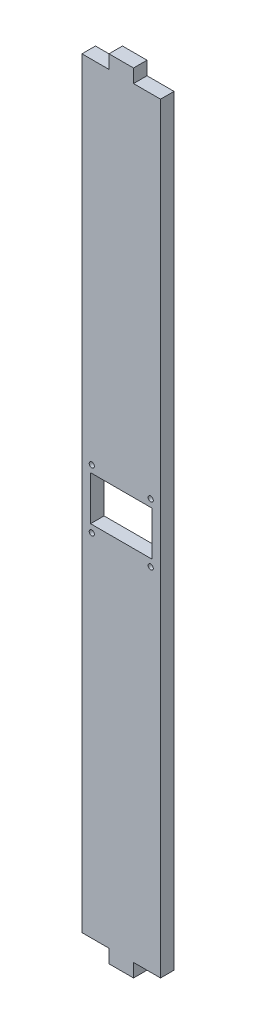
SolidWorks part; units mm, degrees
material "ﾁｰｸ材"
ref_plane "正面" through (0, 0, 0) normal (0, 0, 1) x (1, 0, 0)
ref_plane "平面" through (0, 0, 0) normal (0, 1, 0) x (1, 0, 0)
ref_plane "右側面" through (0, 0, 0) normal (1, 0, 0) x (0, 0, -1)
sketch "ｽｹｯﾁ1" plane through (0, 0, 0) normal (0, 0, 1) x (1, 0, 0)
  line L1 (-16, 160.5) -> (16, 160.5)
  line L2 (-16, 160.5) -> (-16, -160.5)
  line L3 (-16, -160.5) -> (16, -160.5)
  line L4 (16, 160.5) -> (16, -160.5)
  line L5 (-16, 160.5) -> (16, -160.5) construction
  line L6 (-16, -160.5) -> (16, 160.5) construction
  point P0 (0, 0)
  dimension "D1" = 321
  dimension "D2" = 32
extrude "ﾎﾞｽ - 押し出し1" add sketch "ｽｹｯﾁ1" along normal blind 5.5
sketch "ｽｹｯﾁ2" plane through (0, 0, 5.5) normal (0, 0, 1) x (1, 0, 0)
  line L1 (12.5, 9) -> (-12.5, 9)
  line L2 (12.5, 9) -> (12.5, -9)
  line L3 (12.5, -9) -> (-12.5, -9)
  line L4 (-12.5, 9) -> (-12.5, -9)
  line L5 (12.5, 9) -> (-12.5, -9) construction
  line L6 (12.5, -9) -> (-12.5, 9) construction
  circle A0 centre (12, 12) radius 1.05
  circle A1 centre (12, -12) radius 1.05
  circle A2 centre (-12, 12) radius 1.05
  circle A3 centre (-12, -12) radius 1.05
  point P0 (0, 0)
  dimension "D3" = 2.1
  dimension "D4" = 12
  dimension "D1" = 25
  dimension "D2" = 18
  dimension "D5" = 12
  dimension "D6" = 12
  dimension "D7" = 12
extrude "ｶｯﾄ - 押し出し1" cut sketch "ｽｹｯﾁ2" against normal through all
sketch "ｽｹｯﾁ3" plane through (0, 0, 5.5) normal (0, 0, 1) x (1, 0, 0)
  line L0 (0, 0) -> (20.0575, 0) construction
  line L1 (-16, 160.5) -> (-5, 160.5)
  line L2 (-16, 160.5) -> (-16, 155)
  line L3 (-16, 155) -> (-5, 155)
  line L4 (-5, 160.5) -> (-5, 155)
  line L5 (16, 160.5) -> (5, 160.5)
  line L6 (16, 160.5) -> (16, 155)
  line L7 (16, 155) -> (5, 155)
  line L8 (5, 160.5) -> (5, 155)
  line L9 (5, -160.5) -> (5, -155)
  line L10 (16, -155) -> (5, -155)
  line L11 (16, -160.5) -> (16, -155)
  line L12 (16, -160.5) -> (5, -160.5)
  line L13 (-5, -160.5) -> (-5, -155)
  line L14 (-16, -155) -> (-5, -155)
  line L15 (-16, -160.5) -> (-16, -155)
  line L16 (-16, -160.5) -> (-5, -160.5)
  dimension "D1" = 11
  dimension "D2" = 11
  dimension "D3" = 5.5
extrude "ｶｯﾄ - 押し出し2" cut sketch "ｽｹｯﾁ3" against normal through all
